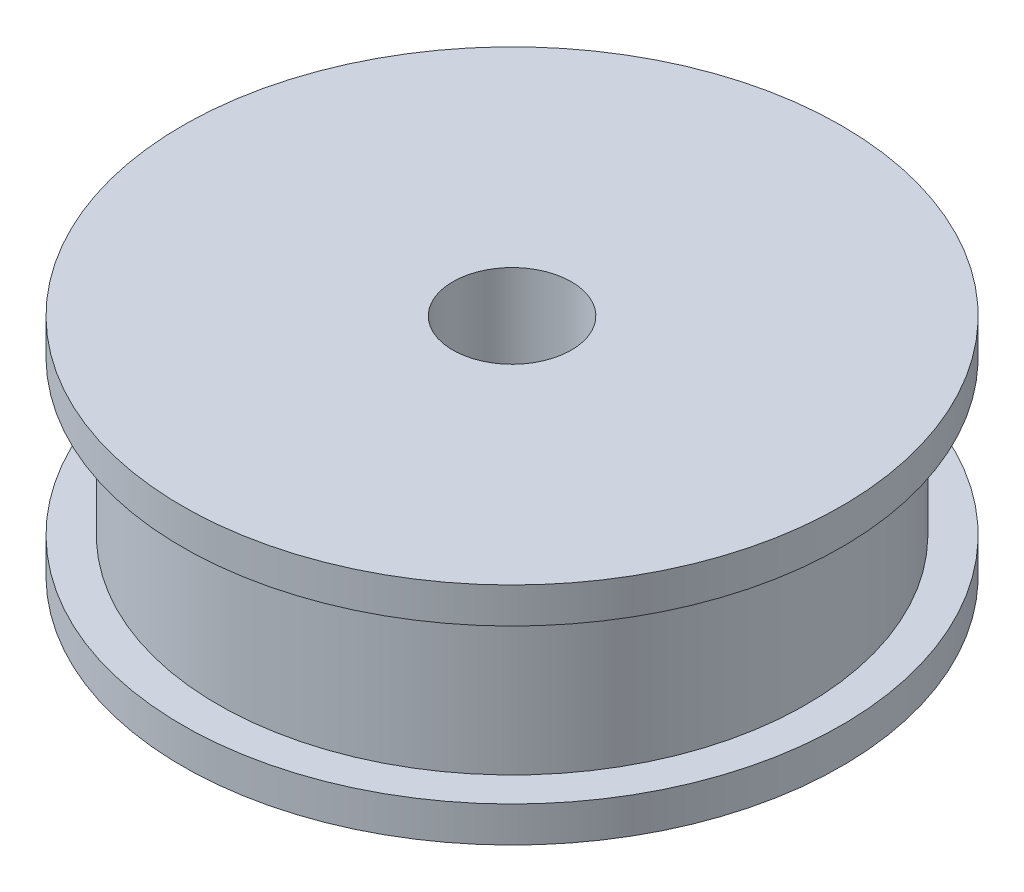
SolidWorks part; units mm, degrees
ref_plane "Face" through (0, 0, 0) normal (0, 0, 1) x (1, 0, 0)
ref_plane "Dessus" through (0, 0, 0) normal (0, 1, 0) x (1, 0, 0)
ref_plane "Droite" through (0, 0, 0) normal (1, 0, 0) x (0, 0, -1)
sketch "Esquisse1" plane through (0, 0, 0) normal (0, 0, 1) x (1, 0, 0)
  line L0 (0, 0) -> (0, 9.7978) construction
  line L1 (2.5, 0) -> (13.9, 0)
  line L2 (13.9, 0) -> (13.9, 1.5)
  line L3 (13.9, 1.5) -> (12.4, 1.5)
  line L4 (12.4, 1.5) -> (12.4, 8)
  line L5 (12.4, 8) -> (13.9, 8)
  line L6 (13.9, 8) -> (13.9, 9.5)
  line L7 (13.9, 9.5) -> (2.5, 9.5)
  line L10 (2.5, 9.5) -> (2.5, 0)
  point P5 (2.5, 9.7978)
  point P12 (3.637, 9.7978)
  point P14 (2.5, 8)
  dimension "D1" = 27.8
  dimension "D2" = 6.5
  dimension "D3" = 5
  dimension "D6" = 1.5
  dimension "D7" = 1.5
  dimension "D8" = 1.5
revolve "Révolution1" add sketch "Esquisse1" angle 360 about L0
